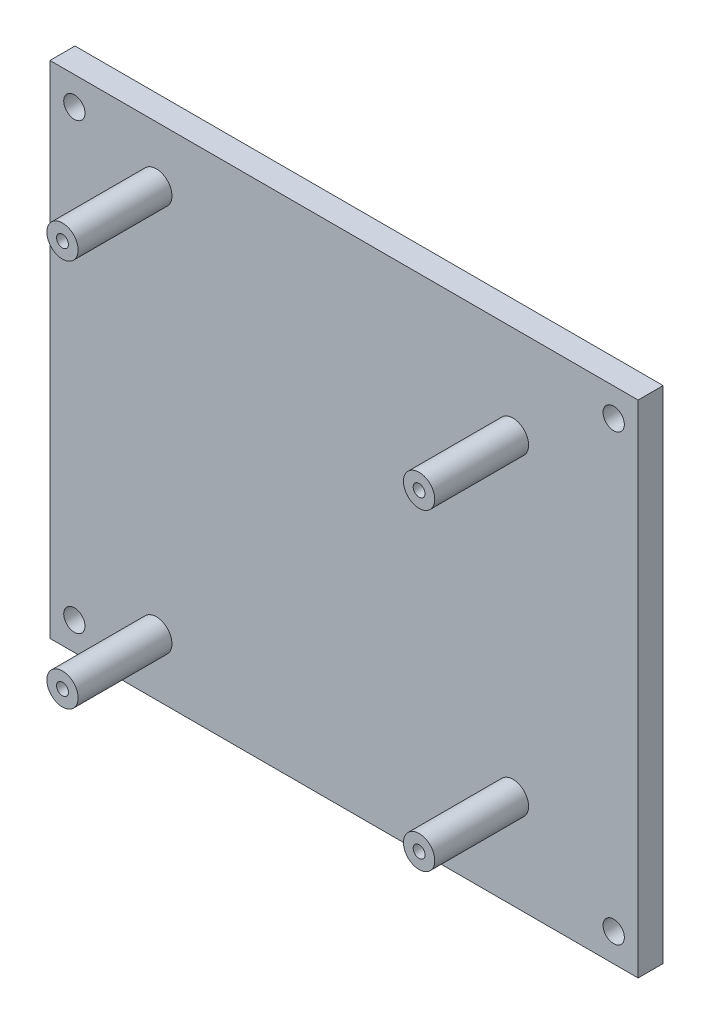
SolidWorks part; units mm, degrees
ref_plane "前视基准面" through (0, 0, 0) normal (0, 0, 1) x (1, 0, 0)
ref_plane "上视基准面" through (0, 0, 0) normal (0, 1, 0) x (1, 0, 0)
ref_plane "右视基准面" through (0, 0, 0) normal (1, 0, 0) x (0, 0, -1)
sketch "草图1" plane through (0, 0, 0) normal (0, 0, 1) x (1, 0, 0)
  line L1 (-47, 40) -> (47, 40)
  line L2 (-47, 40) -> (-47, -40)
  line L3 (-47, -40) -> (47, -40)
  line L4 (47, 40) -> (47, -40)
  line L5 (0, -40) -> (0, 40) construction
  line L6 (-47, 0) -> (47, 0) construction
  point P0 (0, 0)
extrude "凸台-拉伸1" add sketch "草图1" along normal blind 4
sketch "草图2" plane through (0, 0, 4) normal (0, 0, 1) x (1, 0, 0)
  circle A0 centre (-43.1, -35.5) radius 1.7
  circle A1 centre (43.1, -35.5) radius 1.7
  circle A2 centre (43.1, 35.5) radius 1.7
  circle A3 centre (-43.1, 35.5) radius 1.7
  dimension "D1" = 2
  dimension "D2" = 2
extrude "切除-拉伸1" cut sketch "草图2" against normal up to next
sketch "草图3" plane through (0, 0, 4) normal (0, 0, 1) x (1, 0, 0)
  circle A0 centre (-30, 31) radius 2.5
  circle A1 centre (-30, -31) radius 2.5
  circle A2 centre (27, 25) radius 2.5
  circle A3 centre (27, -25) radius 2.5
extrude "凸台-拉伸2" add sketch "草图3" along normal blind 15
sketch "草图4" plane through (0, 0, 19) normal (0, 0, 1) x (1, 0, 0)
  circle A0 centre (-30, 31) radius 0.95
  circle A1 centre (27, 25) radius 0.95
  circle A2 centre (-30, -31) radius 0.95
  circle A3 centre (27, -25) radius 0.95
extrude "切除-拉伸2" cut sketch "草图4" against normal up to next
